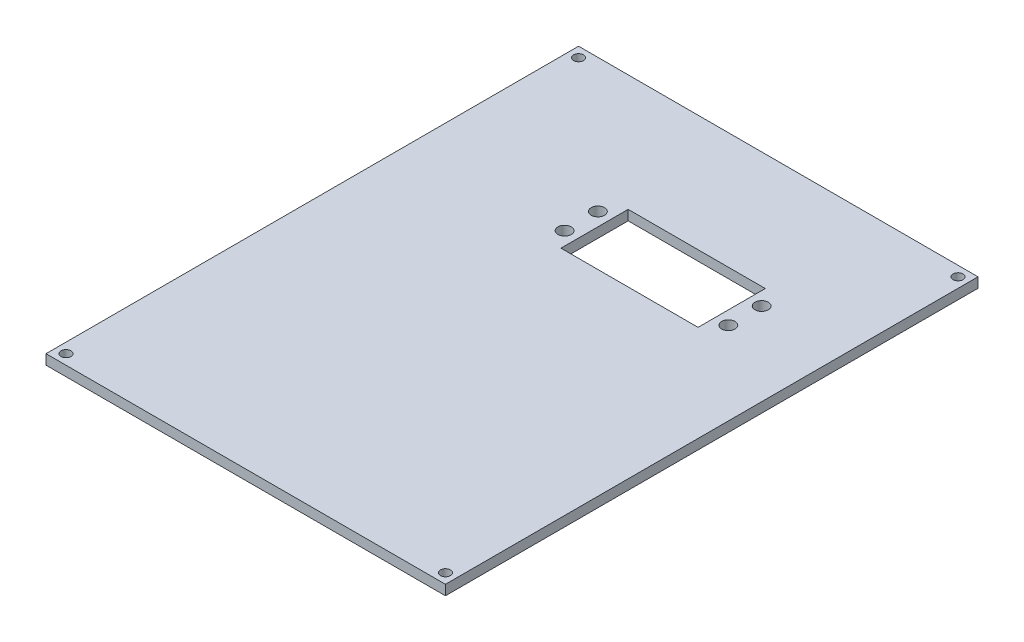
SolidWorks part; units mm, degrees
ref_plane "Front Plane" through (0, 0, 0) normal (0, 0, 1) x (1, 0, 0)
ref_plane "Top Plane" through (0, 0, 0) normal (0, 1, 0) x (1, 0, 0)
ref_plane "Right Plane" through (0, 0, 0) normal (1, 0, 0) x (0, 0, -1)
sketch "Sketch1" plane through (0, 0, 0) normal (0, 1, 0) x (1, 0, 0)
  line L1 (-120, 160) -> (0, 160)
  line L2 (-120, 160) -> (-120, 0)
  line L3 (-120, 0) -> (0, 0)
  line L4 (0, 160) -> (0, 0)
  line L5 (-70.1, 125) -> (-28.9, 125)
  line L6 (-70.1, 125) -> (-70.1, 104.8)
  line L7 (-70.1, 104.8) -> (-28.9, 104.8)
  line L8 (-28.9, 125) -> (-28.9, 104.8)
  circle A0 centre (-117, 157) radius 1.5
  circle A1 centre (-3, 157) radius 1.5
  circle A2 centre (-117, 3) radius 1.5
  circle A3 centre (-3, 3) radius 1.5
  circle A4 centre (-74.1, 119.9) radius 2
  circle A5 centre (-74.1, 109.9) radius 2
  circle A6 centre (-24.9, 119.9) radius 2
  circle A7 centre (-24.9, 109.9) radius 2
  point P25 (0, 0)
  point P26 (0, 0)
  point P27 (0, 0)
  dimension "D3" = 3
  dimension "D4" = 3
  dimension "D5" = 3
  dimension "D6" = 3
  dimension "D15" = 4
  dimension "D16" = 4
  dimension "D17" = 4
  dimension "D18" = 4
  dimension "D1" = 160
  dimension "D2" = 120
  dimension "D7" = 3
  dimension "D8" = 3
  dimension "D9" = 3
  dimension "D10" = 3
  dimension "D11" = 3
  dimension "D12" = 3
  dimension "D13" = 3
  dimension "D14" = 3
  dimension "D19" = 10
  dimension "D20" = 10
  dimension "D21" = 41.2
  dimension "D22" = 20.2
  dimension "D23" = 4
  dimension "D24" = 4
  dimension "D25" = 5.1
  dimension "D26" = 4
  dimension "D27" = 5.1
  dimension "D28" = 4
  dimension "D29" = 35
  dimension "D30" = 49.9
extrude "Boss-Extrude1" add sketch "Sketch1" along normal blind 3
